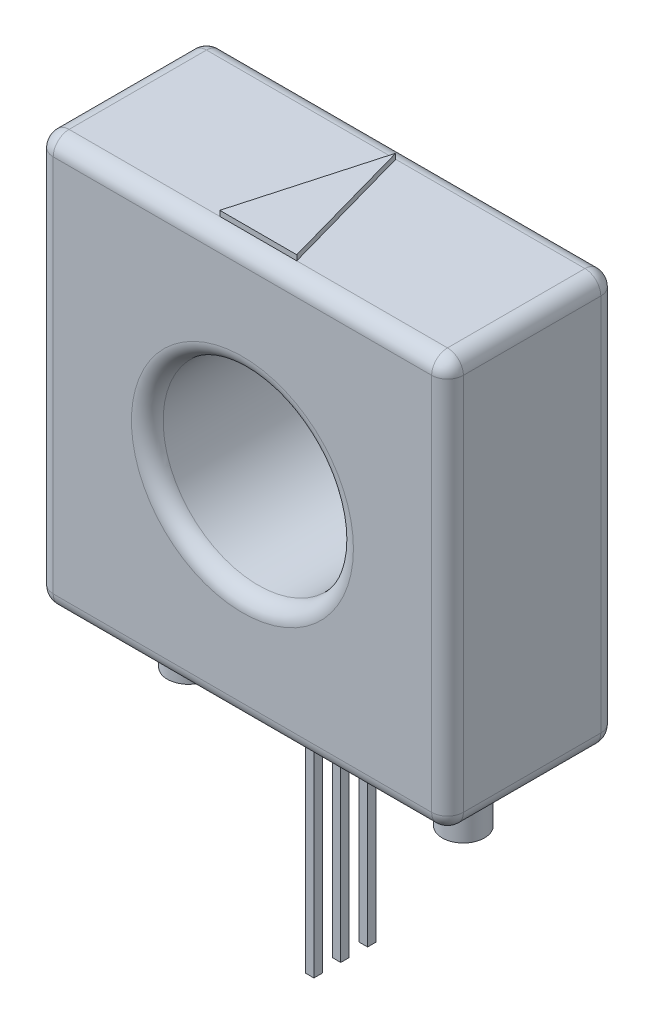
SolidWorks part; units mm, degrees
ref_plane "Front Plane" through (0, 0, 0) normal (0, 0, 1) x (1, 0, 0)
ref_plane "Top Plane" through (0, 0, 0) normal (0, 1, 0) x (1, 0, 0)
ref_plane "Right Plane" through (0, 0, 0) normal (1, 0, 0) x (0, 0, -1)
sketch "Sketch1" plane through (0, 0, 0) normal (0, 0, 1) x (1, 0, 0)
  line L1 (0, 0) -> (19.4, 0)
  line L2 (0, 0) -> (0, -19.4)
  line L3 (0, -19.4) -> (19.4, -19.4)
  line L4 (19.4, 0) -> (19.4, -19.4)
  line L5 (0, 0) -> (19.4, -19.4) construction
  line L6 (0, -19.4) -> (19.4, 0) construction
  circle A0 centre (9.7, -9.7) radius 4.5
  point P4 (9.7, -9.7)
  dimension "D3" = 9
  dimension "D1" = 19.4
  dimension "D2" = 19.4
extrude "Boss-Extrude1" add sketch "Sketch1" along normal blind 8 contours L4 L1 L2 L3 A0
fillet "Fillet1" radius 0.75 14 edges at (19.4, -19.4, 4) (9.7, -19.4, 8) (19.4, -9.7, 8) (14.2, -9.7, 8) (0, -9.7, 8) (0, -19.4, 4) (19.4, 0, 4) (9.7, 0, 8) (0, 0, 4) (9.7, 0, 0) (0, -9.7, 0) (9.7, -19.4, 0) (19.4, -9.7, 0) (14.2, -9.7, 0)
sketch "Sketch2" plane through (0, 0, 0) normal (0, 0, -1) x (-1, 0, 0)
  line L0 (-17.9, -3.7) -> (-0.75, -3.7) construction
  line L1 (-0.75, -18.65) -> (-0.75, -0.75) construction
  line L2 (-17.9, -15.7) -> (-0.75, -15.7) construction
  text T0 "WCS1700-XXXX" font "Century Gothic" height 1.3
  text T1 "+" font "Century Gothic" height 2.5
  point P3 (-9.325, -3.7)
  point P8 (-9.325, -15.7)
extrude "Boss-Extrude2" add sketch "Sketch2" along normal blind 0.01
sketch "Sketch3" plane through (0, 0, 0) normal (0, 1, 0) x (1, 0, 0)
  line L8 (11.52, -7.2504) -> (7.88, -7.25)
  line L10 (0.75, -7.25) -> (18.65, -7.25) construction
  line L11 (7.88, -7.25) -> (9.7, -0.75)
  line L12 (18.65, -0.75) -> (0.75, -0.75) construction
  line L13 (9.7, -0.75) -> (11.52, -7.2504)
  line L14 (9.7, -0.75) -> (9.7, -7.2502) construction
  point P0 (9.7, -1.5)
  point P5 (9.7, -7.2502)
  dimension "D1" = 3.64
  dimension "D2" = 105.641
  dimension "D3" = 90
extrude "Boss-Extrude3" add sketch "Sketch3" along normal blind 0.25 contours L13 L8 L11
sketch "Sketch4" plane through (0, -19.4, 0) normal (0, -1, 0) x (1, 0, 0)
  line L0 (9.7, 0.75) -> (9.7, 7.25) construction
  line L1 (0.75, 0.75) -> (18.65, 0.75) construction
  line L2 (18.65, 7.25) -> (0.75, 7.25) construction
  line L3 (3.2, 3.35) -> (16.2, 3.35) construction
  line L4 (9.5, 4.42) -> (9.9, 4.42)
  line L5 (9.5, 4.42) -> (9.5, 4.82)
  line L7 (9.5, 3.15) -> (9.9, 3.15)
  line L8 (9.5, 3.15) -> (9.5, 3.55)
  line L9 (9.5, 3.55) -> (9.9, 3.55)
  line L10 (9.9, 3.15) -> (9.9, 3.55)
  line L11 (9.5, 3.15) -> (9.9, 3.55) construction
  line L12 (9.5, 3.55) -> (9.9, 3.15) construction
  line L13 (9.5, 4.82) -> (9.9, 4.82)
  line L14 (9.9, 4.42) -> (9.9, 4.82)
  line L15 (9.5, 4.42) -> (9.9, 4.82) construction
  line L16 (9.5, 4.82) -> (9.9, 4.42) construction
  line L17 (9.5, 2.28) -> (9.9, 2.28)
  line L18 (9.5, 2.28) -> (9.5, 1.88)
  line L19 (9.5, 1.88) -> (9.9, 1.88)
  line L20 (9.9, 2.28) -> (9.9, 1.88)
  line L21 (9.5, 2.28) -> (9.9, 1.88) construction
  line L22 (9.5, 1.88) -> (9.9, 2.28) construction
  circle A0 centre (16.2, 4.05) radius 1
  circle A1 centre (16.2, 4.05) radius 0.7
  circle A2 centre (3.2, 4.05) radius 0.7
  circle A3 centre (3.2, 4.05) radius 1
  point P8 (16.2, 4.75)
  point P13 (9.7, 2.08)
  point P18 (9.7, 3.15)
  point P21 (9.7, 4.62)
  dimension "D1" = 2
  dimension "D3" = 1.4
  dimension "D2" = 2.5
  dimension "D4" = 13
  dimension "D5" = 0.4
  dimension "D6" = 0.4
  dimension "D7" = 0.2
  dimension "D8" = 0.2
  dimension "D9" = 0.4
  dimension "D10" = 0.4
  dimension "D11" = 0.87
  dimension "D12" = 0.4
  dimension "D13" = 0.4
  dimension "D14" = 0.87
extrude "Boss-Extrude4" add sketch "Sketch4" along normal blind 3 contours A3 A2 | A0 A1 | L5 L4 L14 L13 | L8 L7 L10 L9 | L18 L17 L20 L19
sketch "Sketch5" plane through (0, -22.4, 0) normal (0, -1, 0) x (1, 0, 0)
  line L1 (9.5, 4.82) -> (9.9, 4.82)
  line L2 (9.5, 4.82) -> (9.5, 4.42)
  line L3 (9.5, 4.42) -> (9.9, 4.42)
  line L4 (9.9, 4.82) -> (9.9, 4.42)
  line L5 (9.5, 4.82) -> (9.9, 4.42) construction
  line L6 (9.5, 4.42) -> (9.9, 4.82) construction
  line L7 (9.5, 3.55) -> (9.9, 3.55)
  line L8 (9.5, 3.55) -> (9.5, 3.15)
  line L9 (9.5, 3.15) -> (9.9, 3.15)
  line L10 (9.9, 3.55) -> (9.9, 3.15)
  line L11 (9.5, 3.55) -> (9.9, 3.15) construction
  line L12 (9.5, 3.15) -> (9.9, 3.55) construction
  line L13 (9.5, 2.28) -> (9.9, 2.28)
  line L14 (9.5, 2.28) -> (9.5, 1.88)
  line L15 (9.5, 1.88) -> (9.9, 1.88)
  line L16 (9.9, 2.28) -> (9.9, 1.88)
  line L17 (9.5, 2.28) -> (9.9, 1.88) construction
  line L18 (9.5, 1.88) -> (9.9, 2.28) construction
  point P4 (9.7, 4.62)
  point P11 (9.7, 3.35)
  point P18 (9.7, 2.08)
extrude "Boss-Extrude5" add sketch "Sketch5" along normal blind 9
